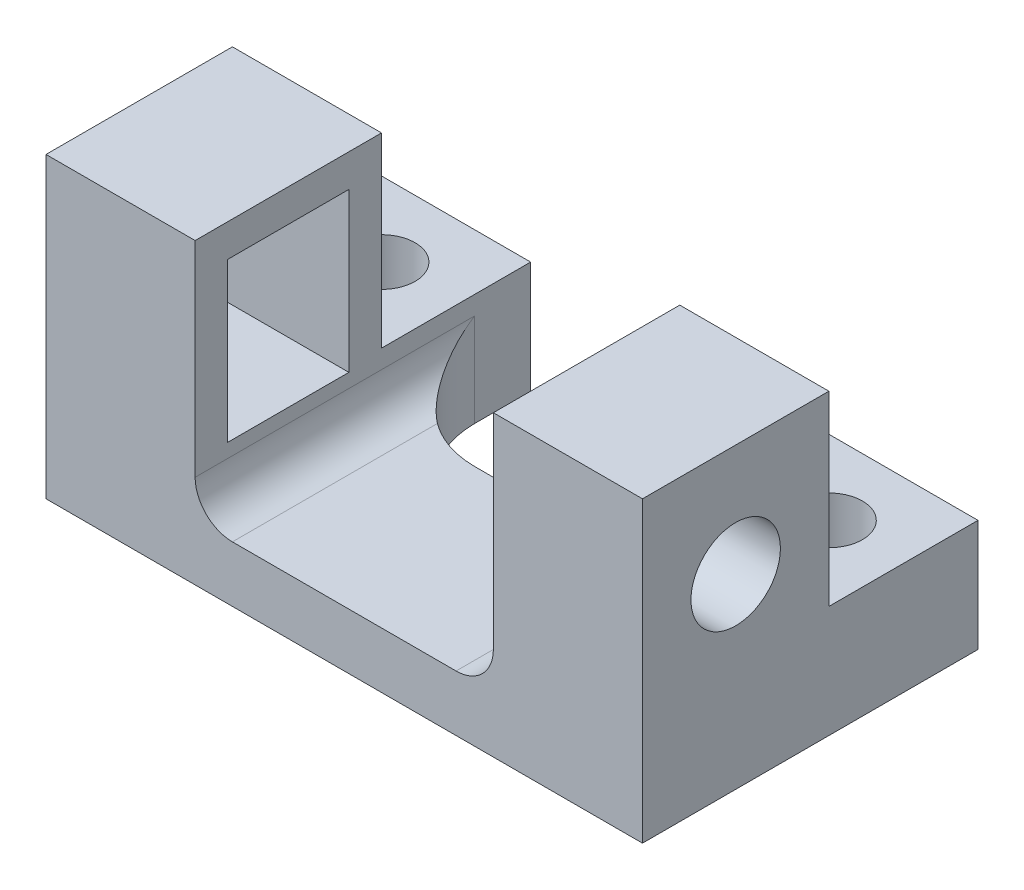
SolidWorks part; units mm, degrees
ref_plane "Front Plane" through (0, 0, 0) normal (0, 0, 1) x (1, 0, 0)
ref_plane "Top Plane" through (0, 0, 0) normal (0, 1, 0) x (1, 0, 0)
ref_plane "Right Plane" through (0, 0, 0) normal (1, 0, 0) x (0, 0, -1)
sketch "Sketch1" plane through (0, 0, 0) normal (0, 1, 0) x (1, 0, 0)
  line L1 (-8, -2.5) -> (8, -2.5)
  line L2 (-8, -2.5) -> (-8, 2.5)
  line L3 (-8, 2.5) -> (8, 2.5)
  line L4 (8, -2.5) -> (8, 2.5)
  line L5 (-8, -2.5) -> (8, 2.5) construction
  line L6 (-8, 2.5) -> (8, -2.5) construction
  point P0 (0, 0)
  dimension "D1" = 5
  dimension "D2" = 16
extrude "Boss-Extrude1" add sketch "Sketch1" along normal mid plane 8
sketch "Sketch2" plane through (0, 4, 5) normal (0, -1, 0) x (1, 0, 0)
  line L0 (8, -7.5) -> (-8, -7.5) construction
  line L1 (-4, -2.5) -> (4, -2.5)
  line L2 (-4, -2.5) -> (-4, -7.5)
  line L3 (-4, -7.5) -> (4, -7.5)
  line L4 (4, -2.5) -> (4, -7.5)
  line L5 (-4, -2.5) -> (4, -7.5) construction
  line L6 (-4, -7.5) -> (4, -2.5) construction
  line L7 (-8, -7.5) -> (-8, -2.5) construction
  point P0 (0, -5)
  dimension "D1" = 4
extrude "Cut-Extrude1" cut sketch "Sketch2" along normal blind 6.5
sketch "Sketch3" plane through (-8, 0, 0) normal (-1, 0, 0) x (0, 0, 1)
  line L19 (-2.5, 4) -> (2.5, 4) construction
  line L20 (-1.625, 3.125) -> (1.625, 3.125)
  line L21 (-1.625, 3.125) -> (-1.625, -1.125)
  line L22 (-1.625, -1.125) -> (1.625, -1.125)
  line L23 (1.625, 3.125) -> (1.625, -1.125)
  line L24 (0, -1.125) -> (0, 3.125) construction
  point P9 (0, 1)
  dimension "D1" = 4.25
  dimension "D2" = 3
  dimension "D3" = 3.25
extrude "Cut-Extrude2" cut sketch "Sketch3" against normal up to surface (4 mm away) up to face at (-4, 0.75, 0)
sketch "Sketch7" plane through (8, 0, 0) normal (1, 0, 0) x (0, 0, -1)
  line L0 (-2.5, 4) -> (2.5, 4) construction
  point P0 (0, 1)
  dimension "D1" = 3
hole_wizard "M2 Clearance Hole2" positions "Sketch8" profile "Sketch9" hole size "M2" standard "ISO"
sketch "Sketch8" plane through (8, 0, 0) normal (1, 0, 0) x (0, 0, -1)
  point P0 (0, 1)
sketch "Sketch9" plane through (8, 1, 0) normal (0, 1, 0) x (0, 0, -1)
  line L0 (0, 0) -> (0, 4.721)
  line L1 (0, 4.721) -> (1.2, 4)
  line L2 (1.2, 4) -> (1.2, 0)
  line L5 (1.2, 0) -> (0, 0)
  line L10 (0, 4.721) -> (-1.2, 4) construction
  line L11 (0, -6.35) -> (0, 107.95) construction
  dimension "Hole Dia." = 2.4
  dimension "Hole Depth" = 4
  dimension "Drill Angle" = 118
sketch "Sketch10" plane through (0, -4, 0) normal (0, -1, 0) x (1, 0, 0)
  line L1 (8, -2.5) -> (4, -2.5)
  line L2 (8, -2.5) -> (8, -6.5)
  line L3 (8, -6.5) -> (4, -6.5)
  line L4 (4, -2.5) -> (4, -6.5)
  line L5 (-8, -2.5) -> (-4, -2.5)
  line L6 (-8, -2.5) -> (-8, -6.5)
  line L7 (-8, -6.5) -> (-4, -6.5)
  line L8 (-4, -2.5) -> (-4, -6.5)
  dimension "D1" = 4
  dimension "D2" = 4
extrude "Boss-Extrude2" add sketch "Sketch10" against normal blind 3
sketch "Sketch11" plane through (0, -1, 0) normal (0, 1, 0) x (1, 0, 0)
  line L0 (4, 6.5) -> (8, 6.5) construction
  line L1 (-8, 6.5) -> (-4, 6.5) construction
  line L2 (8, 6.5) -> (8, 2.5) construction
  point P0 (6, 4.5)
  point P1 (-6, 4.5)
  point P4 (0, 0)
  point P5 (6, 6.5)
  point P6 (0, 0)
  point P9 (-6, 6.5)
  point P12 (8, 4.5)
hole_wizard "M1.6 Clearance Hole1" positions "Sketch12" profile "Sketch13" hole size "M1.6" standard "ISO"
sketch "Sketch12" plane through (0, -1, 0) normal (0, 1, 0) x (1, 0, 0)
  point P0 (6, 4.5)
  point P3 (-6, 4.5)
sketch "Sketch13" plane through (6, -1, -4.5) normal (1, 0, 0) x (0, 0, 1)
  line L0 (0, 0) -> (0, 4.5408)
  line L1 (0, 4.5408) -> (0.9, 4)
  line L2 (0.9, 4) -> (0.9, 0)
  line L5 (0.9, 0) -> (0, 0)
  line L10 (0, 4.5408) -> (-0.9, 4) construction
  line L11 (0, -6.35) -> (0, 107.95) construction
  dimension "Hole Dia." = 1.8
  dimension "Hole Depth" = 4
  dimension "Drill Angle" = 118
fillet "Fillet1" radius 1 2 edges at (-4, -2.5, 0) (4, -2.5, 0)
fillet "Fillet2" radius 2.5 2 edges at (-4, -2.75, -2.5) (4, -2.75, -2.5)
